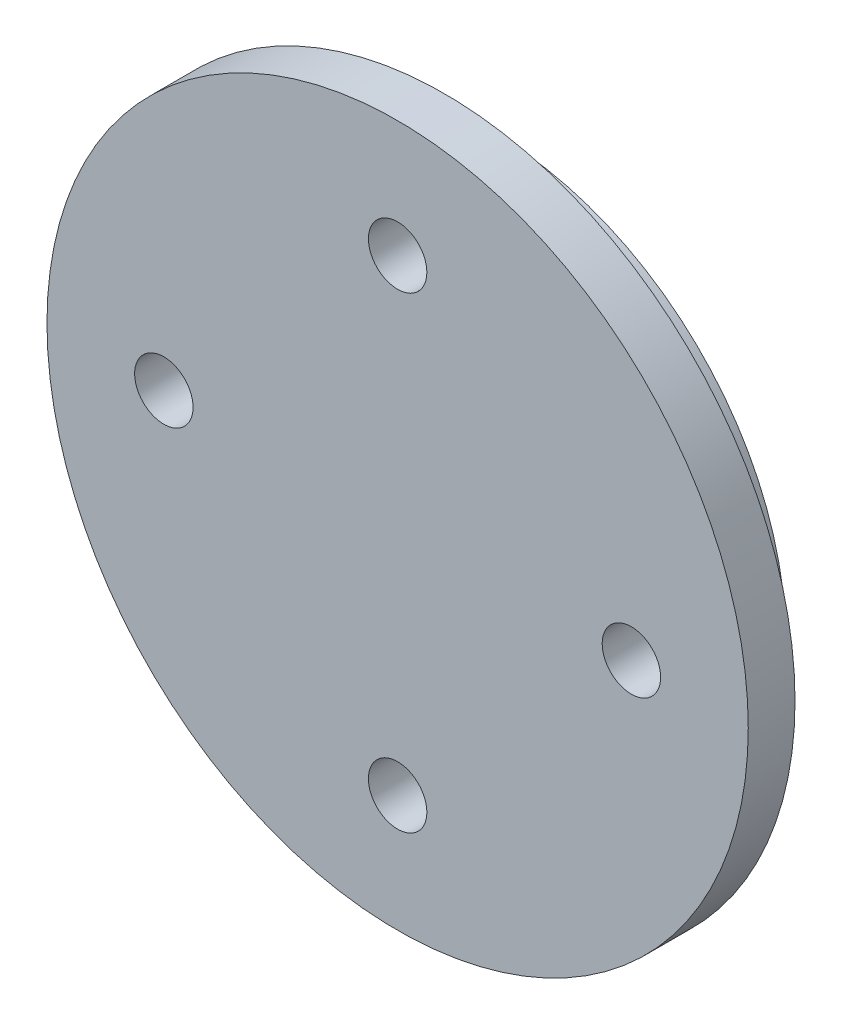
SolidWorks part; units mm, degrees
ref_plane "Front Plane" through (0, 0, 0) normal (0, 0, 1) x (1, 0, 0)
ref_plane "Top Plane" through (0, 0, 0) normal (0, 1, 0) x (1, 0, 0)
ref_plane "Right Plane" through (0, 0, 0) normal (1, 0, 0) x (0, 0, -1)
sketch "Sketch1" plane through (0, 0, 0) normal (0, 0, 1) x (1, 0, 0)
  circle A0 centre (0, 0) radius 31.75
  dimension "D1" = 63.5
extrude "Boss-Extrude1" add sketch "Sketch1" along normal blind 5.334
sketch "Sketch2" plane through (0, 0, 5.334) normal (0, 0, 1) x (1, 0, 0)
  circle A0 centre (0, 0) radius 38.1
  dimension "D1" = 76.2
extrude "Boss-Extrude2" add sketch "Sketch2" along normal blind 5.08 contours A0
sketch "Sketch3" plane through (0, 0, 10.414) normal (0, 0, 1) x (1, 0, 0)
  circle A0 centre (0, 25.4) radius 3.175
  point P2 (0, 25.4)
  dimension "D1" = 6.35
  dimension "D2" = 25.4
extrude "Cut-Extrude1" cut sketch "Sketch3" against normal through all
pattern_circular "CirPattern1" count 4 over 360 about axis through (0, 0, 0) along (0, 0, 1) of "Cut-Extrude1"
sketch "Sketch6" plane through (0, 0, 0) normal (0, 0, -1) x (-1, 0, 0)
  circle A0 centre (-5.08, 0) radius 1.27
  dimension "D1" = 2.54
  dimension "D2" = 5.08
extrude "Cut-Extrude3" cut sketch "Sketch6" against normal up to surface (5.334 mm away) up to face at (31.75, 0, 5.334)
pattern_circular "CirPattern2" count 4 over 360 about axis through (0, 0, 0) along (0, 0, 1) of "Cut-Extrude3"
